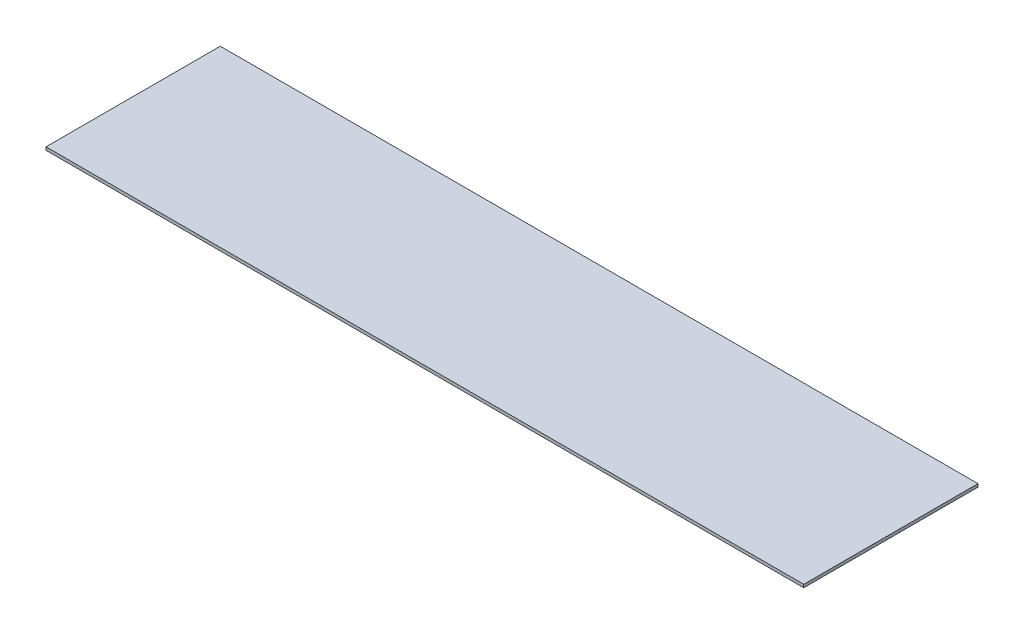
SolidWorks part; units mm, degrees
ref_plane "Front Plane" through (0, 0, 0) normal (0, 0, 1) x (1, 0, 0)
ref_plane "Top Plane" through (0, 0, 0) normal (0, 1, 0) x (1, 0, 0)
ref_plane "Right Plane" through (0, 0, 0) normal (1, 0, 0) x (0, 0, -1)
sketch "Sketch1" plane through (0, 0, 0) normal (0, 1, 0) x (1, 0, 0)
  line L1 (-176.5123, 119.0926) -> (323.4877, 119.0926)
  line L2 (-176.5123, 119.0926) -> (-176.5123, 4.0926)
  line L3 (-176.5123, 4.0926) -> (323.4877, 4.0926)
  line L4 (323.4877, 119.0926) -> (323.4877, 4.0926)
  dimension "D1" = 500
  dimension "D2" = 115
extrude "Boss-Extrude1" add sketch "Sketch1" along normal blind 2
equation "\"clip_tube_diam\"= 6mm"
equation "\"middle_tube_len\"= 500mm"
equation "\"horizontal_pipe_spacing\"= 260mm"
equation "\"belly_plate_width\" = 176mm"
